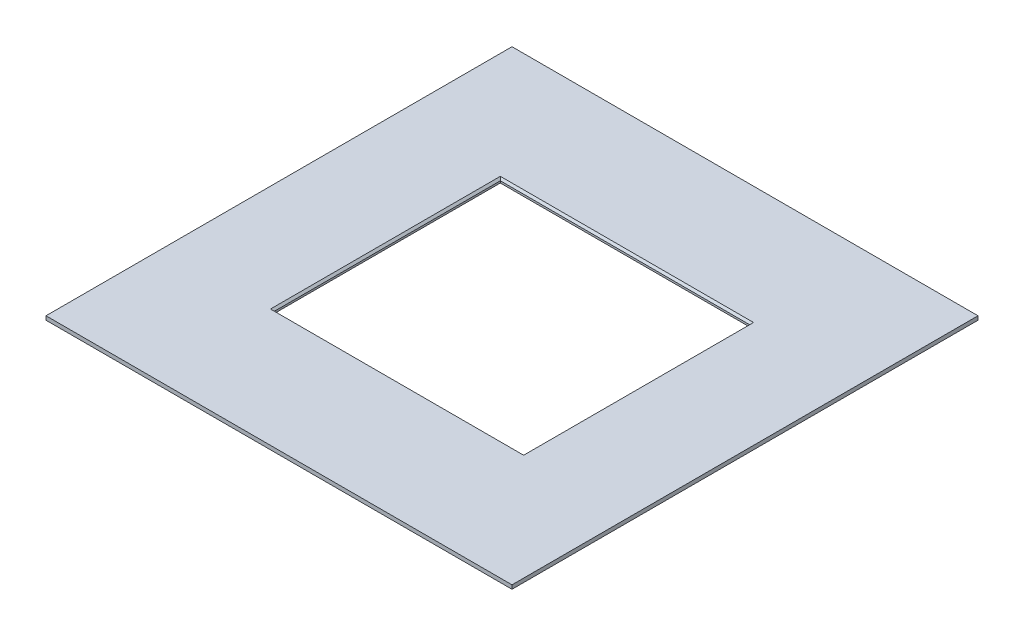
SolidWorks part; units mm, degrees
ref_plane "Front Plane" through (0, 0, 0) normal (0, 0, 1) x (1, 0, 0)
ref_plane "Top Plane" through (0, 0, 0) normal (0, 1, 0) x (1, 0, 0)
ref_plane "Right Plane" through (0, 0, 0) normal (1, 0, 0) x (0, 0, -1)
sketch "Sketch1" plane through (0, 0, 0) normal (0, 1, 0) x (1, 0, 0)
  line L1 (-60, 60) -> (60, 60)
  line L2 (-60, 60) -> (-60, -60)
  line L3 (-60, -60) -> (60, -60)
  line L4 (60, 60) -> (60, -60)
  line L5 (-60, 60) -> (60, -60) construction
  line L6 (-60, -60) -> (60, 60) construction
  line L7 (-32.1, 29.1) -> (32.1, 29.1)
  line L8 (-32.1, 29.1) -> (-32.1, -29.1)
  line L9 (-32.1, -29.1) -> (32.1, -29.1)
  line L10 (32.1, 29.1) -> (32.1, -29.1)
  line L11 (-32.1, 29.1) -> (32.1, -29.1) construction
  line L12 (-32.1, -29.1) -> (32.1, 29.1) construction
  point P0 (0, 0)
  point P6 (0, 0)
  dimension "D1" = 120
  dimension "D2" = 120
  dimension "D3" = 64.2
  dimension "D4" = 58.2
extrude "Boss-Extrude1" add sketch "Sketch1" along normal blind 1
chamfer "Chamfer1" distance 0.5 angle 45 4 edges at (0, 1, 29.1) (32.1, 1, 0) (-32.1, 1, 0) (0, 1, -29.1)
